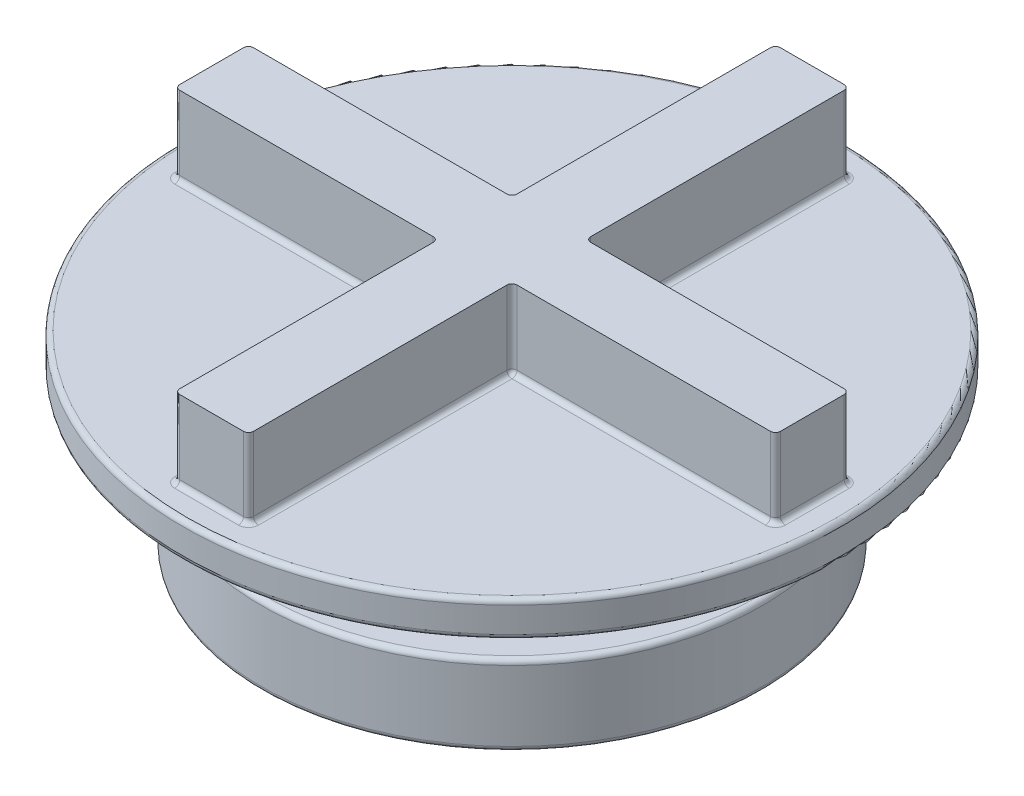
SolidWorks part; units mm, degrees
material "PET"
ref_plane "Front Plane" through (0, 0, 0) normal (0, 0, 1) x (1, 0, 0)
ref_plane "Top Plane" through (0, 0, 0) normal (0, 1, 0) x (1, 0, 0)
ref_plane "Right Plane" through (0, 0, 0) normal (1, 0, 0) x (0, 0, -1)
sketch "Main Body Sketch" plane through (0, 0, 0) normal (0, 0, 1) x (1, 0, 0)
  line L1 (-9, -26.665) -> (9, -26.665)
  line L2 (-9, -26.665) -> (-9, 26.665)
  line L3 (-9, 26.665) -> (9, 26.665)
  line L4 (9, -26.665) -> (9, 26.665)
  line L5 (-9, -26.665) -> (9, 26.665) construction
  line L6 (-9, 26.665) -> (9, -26.665) construction
  point P0 (0, 0)
  dimension "D1" = 53.33
  dimension "D2" = 18
extrude "Half Main Body Extrude" add sketch "Main Body Sketch" along normal mid plane 2.21 contours L3 L4 L1 L2
move or copy body "Half Main Body Copy" bodies to move or copy 101 copy yes number of copies 1 rotation origin (0, 0, 0) rotation axis (0, 1, 0) rotation angle 90 parameters "Pitch"=0, "Yaw"=90, "Roll"=0
sketch "Bottom Base Sketch" plane through (0, 26.665, 0) normal (0, 1, 0) x (1, 0, 0)
  circle A0 centre (0, 0) radius 13
  dimension "D1" = 26
extrude "Bottom Base Extrude" add sketch "Bottom Base Sketch" along normal blind 2.71
sketch "Protrusions Sketch" plane through (0, 29.375, 0) normal (0, 1, 0) x (1, 0, 0)
  line L1 (-0.94, -8.65) -> (0.94, -8.65)
  line L2 (-0.94, -8.65) -> (-0.94, 8.65)
  line L3 (-0.94, 8.65) -> (0.94, 8.65)
  line L4 (0.94, -8.65) -> (0.94, 8.65)
  line L5 (-0.94, -8.65) -> (0.94, 8.65) construction
  line L6 (-0.94, 8.65) -> (0.94, -8.65) construction
  point P0 (0, 0)
  dimension "D1" = 1.88
  dimension "D2" = 17.3
extrude "Protrusions Extrude" add sketch "Protrusions Sketch" along normal blind 0.97 contours L2 L1 L4 L3
fillet "Protrusions Smoothing" radius 0.9 8 edges at (0.94, 29.86, -8.65) (-0.94, 29.86, -8.65) (0, 30.345, -8.65) (0.94, 30.345, 0) (0.94, 29.86, 8.65) (0, 30.345, 8.65) (-0.94, 29.86, 8.65) (-0.94, 30.345, 0)
fillet "Protrusions Smoothing Platform" radius 0.1 8 edges at (0, 29.375, 8.65) (0, 29.375, -8.65) (0.6764, 29.375, -8.3864) (0.94, 29.375, 0) (0.6764, 29.375, 8.3864) (-0.6764, 29.375, -8.3864) (-0.6764, 29.375, 8.3864) (-0.94, 29.375, 0)
sketch "Orthogonal Protrusions Axis" plane through (0, 29.375, 0) normal (0, 1, 0) x (1, 0, 0)
  line L0 (-13, 0) -> (13, 0) construction
  circle A0 centre (0, 0) radius 13 construction
pattern_linear "LPattern1" count 3 spacing 3.76 along (1, 0, 0) count 3 spacing 3.76 along (-1, 0, 0) of "Protrusions Smoothing", "Protrusions Smoothing Platform", "Protrusions Extrude"
sketch "Top Base Sketch" plane through (0, -26.665, 0) normal (0, -1, 0) x (-1, 0, 0)
  circle A0 centre (0, 0) radius 9.875
  dimension "D1" = 19.75
extrude "Top Base Extrude" add sketch "Top Base Sketch" along normal blind 1.06 contours A0
sketch "Top Intermediate Sketch" plane through (0, -27.725, 0) normal (0, -1, 0) x (-1, 0, 0)
  circle A0 centre (0, 0) radius 5.99
  dimension "D1" = 11.98
extrude "Top Intermediate Base Extrude" add sketch "Top Intermediate Sketch" along normal blind 2.18 contours A0
sketch "Outer Base Sketch" plane through (0, -29.905, 0) normal (0, -1, 0) x (-1, 0, 0)
  circle A0 centre (0, 0) radius 7.505
  dimension "D1" = 15.01
extrude "Outer Base Extrude" add sketch "Outer Base Sketch" along normal blind 2.4
fillet "Smoothing Fillets" radius 0.15 42 edges at (9, 0, 1.105) (0, 26.665, 13) (0, 29.375, 13) (-5.0525, -26.665, 1.105) (5.0525, 26.665, -1.105) (5.0525, 26.665, 1.105) (-1.105, 26.665, -5.0525) (1.105, 26.665, -5.0525) (5.0525, -26.665, -1.105) (5.0525, -26.665, 1.105) (0, -26.665, -9.875) (0, -27.725, -9.875) (0, -29.905, -7.505) (0, -32.305, -7.505) (-1.105, -26.665, 5.0525) (0, -26.665, 9) (1.105, 26.665, 5.0525) (1.105, -26.665, 5.0525) (1.105, 0, 1.105) (1.105, 0, -1.105) (-1.105, 0, 9) (-1.105, 26.665, 5.0525) (-1.105, 0, 1.105) (1.105, 0, 9) (0, 26.665, 9) (-1.105, -26.665, -5.0525) (-1.105, 0, -9) (0, -26.665, -9) (0, 26.665, -9) (1.105, -26.665, -5.0525) (1.105, 0, -9) (-1.105, 0, -1.105) (-9, 0, 1.105) (-5.0525, -26.665, -1.105) (9, 0, -1.105) (-5.0525, 26.665, -1.105) (-9, 0, -1.105) (-9, -26.665, 0) (9, -26.665, 0) (9, 26.665, 0) (-9, 26.665, 0) (-5.0525, 26.665, 1.105)
ref_plane "Plane1" through (0, -24.305, 0) normal (0, -1, 0) x (-1, 0, 0)
sketch "Sketch2" plane through (0, -24.305, 0) normal (0, -1, 0) x (-1, 0, 0)
  line L1 (-19.3291, 15.6134) -> (18.9142, 15.6134)
  line L2 (-19.3291, 15.6134) -> (-19.3291, -15.6477)
  line L3 (-19.3291, -15.6477) -> (18.9142, -15.6477)
  line L4 (18.9142, 15.6134) -> (18.9142, -15.6477)
extrude "Cut-Extrude1" cut sketch "Sketch2" against normal through all
